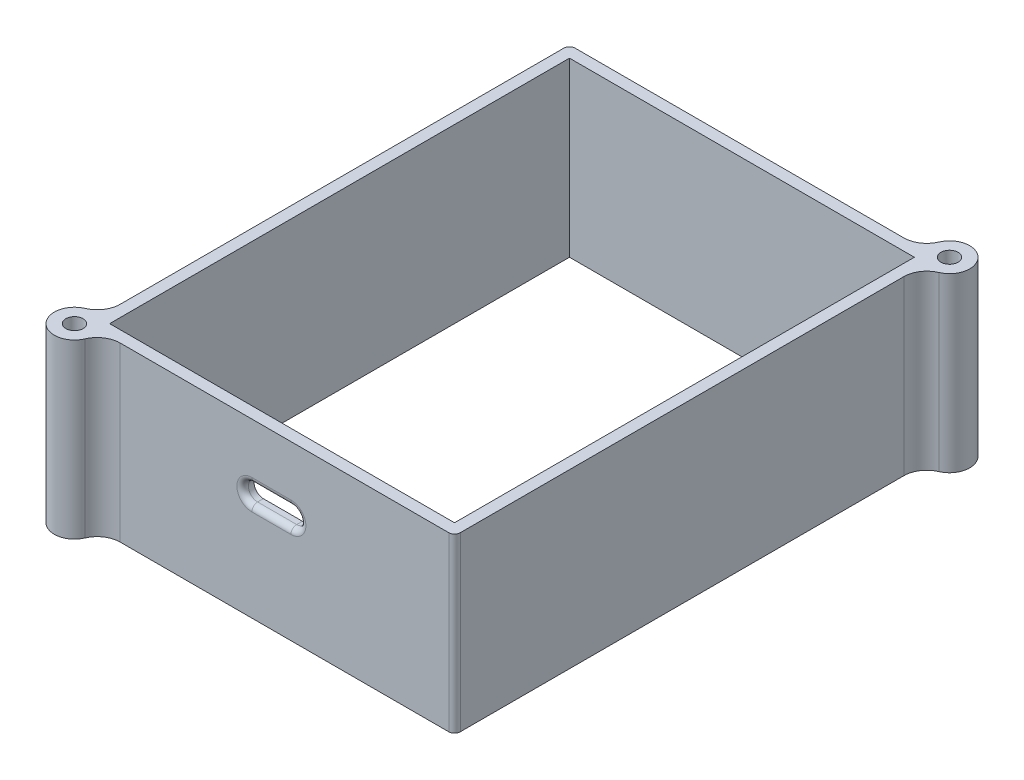
SolidWorks part; units mm, degrees
ref_plane "Front Plane" through (0, 0, 0) normal (0, 0, 1) x (1, 0, 0)
ref_plane "Top Plane" through (0, 0, 0) normal (0, 1, 0) x (1, 0, 0)
ref_plane "Right Plane" through (0, 0, 0) normal (1, 0, 0) x (0, 0, -1)
sketch "Sketch1" plane through (0, 0, 0) normal (0, 1, 0) x (1, 0, 0)
  line L0 (0, 0) -> (60, 0)
  line L1 (60, 0) -> (60, -80)
  line L2 (60, -80) -> (0, -80)
  line L3 (0, -80) -> (0, 0)
  line L4 (-2, -82) -> (-2, 2)
  line L5 (-2, 2) -> (62, 2)
  line L6 (62, 2) -> (62, -82)
  line L7 (62, -82) -> (-2, -82)
  dimension "D1" = 60
  dimension "D2" = 80
  dimension "D3" = 2
extrude "Boss-Extrude1" add sketch "Sketch1" along normal blind 30
ref_plane "HOLE_MIRROR_PLANE" through (-0.3013, 0, 0.2296) normal (0.7954, 0, -0.606) x (-0.606, 0, -0.7954)
sketch "Sketch2" plane through (0, 0, 0) normal (0, 1, 0) x (1, 0, 0)
  line L0 (-2, -82) -> (-6.2426, -86.2426) construction
  line L1 (-6.2426, -86.2426) -> (-3.0607, -83.0607) construction
  line L7 (62, 2) -> (66.2426, 6.2426) construction
  line L8 (66.2426, 6.2426) -> (63.0607, 3.0607) construction
  circle A0 centre (-3.0607, -83.0607) radius 1.5
  circle A1 centre (-3.0607, -83.0607) radius 3.5
  circle A2 centre (63.0607, 3.0607) radius 1.5
  circle A3 centre (63.0607, 3.0607) radius 3.5
  dimension "D3" = 3
  dimension "D4" = 7
  dimension "D7" = 3
  dimension "D8" = 7
  dimension "D1" = 6
  dimension "D2" = 4.5
  dimension "D5" = 6
  dimension "D6" = 4.5
extrude "Boss-Extrude2" add sketch "Sketch2" along normal blind 30
ref_plane "USBC_HOLE_PLANE" through (0, 0, 82) normal (0, 0, 1) x (1, 0, 0)
sketch "Sketch4" plane through (0, 0, 82) normal (0, 0, 1) x (1, 0, 0)
  line L0 (30.1413, 0) -> (30.1413, 17) construction
  line L1 (0.2748, 0) -> (62, 0) construction
  line L2 (30.1413, 17) -> (30.1413, 18.6) construction
  line L3 (30.1413, 18.6) -> (25.1413, 18.6) construction
  line L4 (30.1413, 18.6) -> (30.1413, 20.2) construction
  line L5 (25.1413, 18.6) -> (26.7413, 18.6) construction
  line L6 (30.1413, 20.2) -> (26.7413, 20.2)
  line L7 (30.1413, 17) -> (26.7413, 17)
  line L8 (30.1413, 18.6) -> (35.1413, 18.6) construction
  line L9 (35.1413, 18.6) -> (33.5413, 18.6) construction
  line L10 (30.1413, 20.2) -> (33.5413, 20.2)
  line L11 (30.1413, 17) -> (33.5413, 17)
  arc A0 (26.7413, 17) -> (26.7413, 20.2) centre (26.7413, 18.6) cw
  arc A1 (33.5413, 20.2) -> (33.5413, 17) centre (33.5413, 18.6) cw
  dimension "D1" = 17
  dimension "D2" = 1.6
  dimension "D3" = 5
  dimension "D4" = 1.6
  dimension "D5" = 1.6
  dimension "D6" = 5
  dimension "D7" = 1.6
extrude "Cut-Extrude1" cut sketch "Sketch4" against normal blind 30
fillet "Fillet2" radius 1 4 edges at (25.1413, 18.6, 82) (30.1413, 20.2, 82) (35.1413, 18.6, 82) (30.1413, 17, 82)
fillet "Fillet3" radius 4 4 edges at (62, 15, 0.2748) (59.7252, 15, -2) (-2, 15, 79.7252) (0.2748, 15, 82)
fillet "Fillet4" radius 1 2 edges at (-2, 15, -2) (62, 15, 82)
